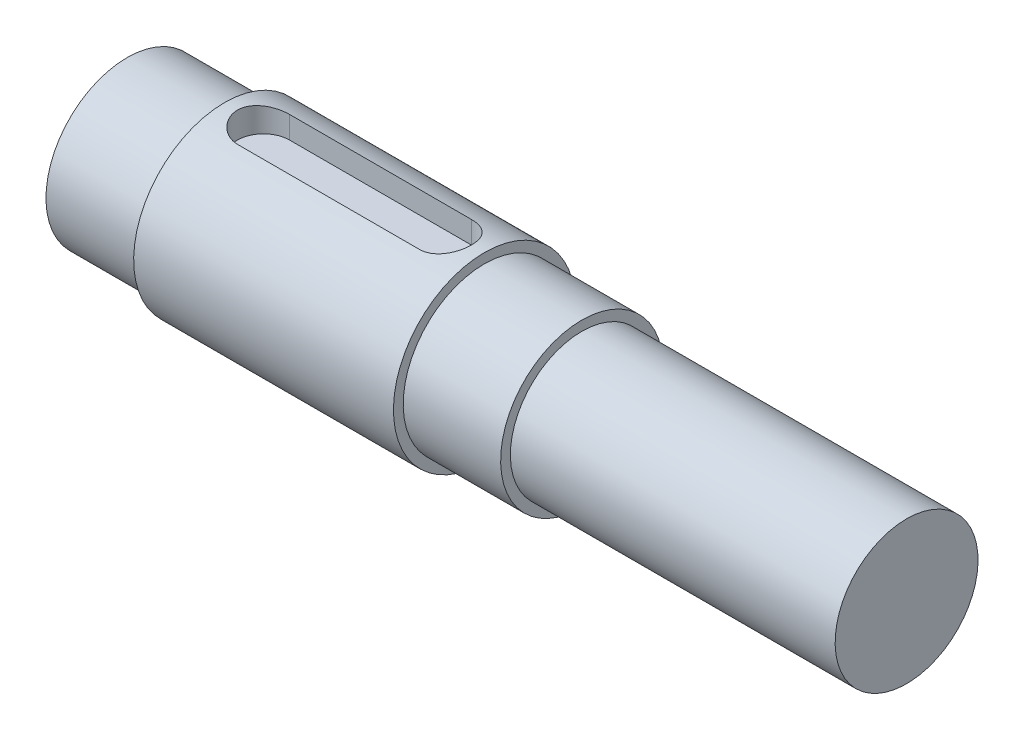
SolidWorks part; units mm, degrees
ref_plane "Спереди" through (0, 0, 0) normal (0, 0, 1) x (1, 0, 0)
ref_plane "Сверху" through (0, 0, 0) normal (0, 1, 0) x (1, 0, 0)
ref_plane "Справа" through (0, 0, 0) normal (1, 0, 0) x (0, 0, -1)
sketch "Эскиз1" plane through (0, 0, 0) normal (0, 0, 1) x (1, 0, 0)
  line L0 (0, 0) -> (0, 12.5)
  line L1 (0, 12.5) -> (15, 12.5)
  line L2 (15, 12.5) -> (15, 14)
  line L3 (15, 14) -> (55, 14)
  line L4 (55, 14) -> (55, 12.5)
  line L5 (55, 12.5) -> (70, 12.5)
  line L6 (70, 12.5) -> (70, 11)
  line L7 (70, 11) -> (120, 11)
  line L8 (120, 11) -> (120, 0)
  line L9 (120, 0) -> (0, 0)
  line L10 (0, 0) -> (120, 0) construction
  dimension "D1" = 120
  dimension "D2" = 14
  dimension "D3" = 12.5
  dimension "D4" = 12.5
  dimension "D5" = 11
  dimension "D6" = 15
  dimension "D7" = 40
  dimension "D8" = 50
revolve "Повернуть1" add sketch "Эскиз1" angle 360 about L9
sketch "Эскиз3" plane through (0, 0, 0) normal (0, 1, 0) x (1, 0, 0)
  line L2 (21, 0) -> (49, 0) construction
  line L4 (21, 4) -> (49, 4)
  line L5 (21, -4) -> (49, -4)
  arc A0 (21, 4) -> (21, -4) centre (21, 0) ccw
  arc A1 (49, -4) -> (49, 4) centre (49, 0) ccw
  point P8 (35, 0)
extrude "Вырез-Вытянуть1" cut sketch "Эскиз3" along normal through all from offset 10
